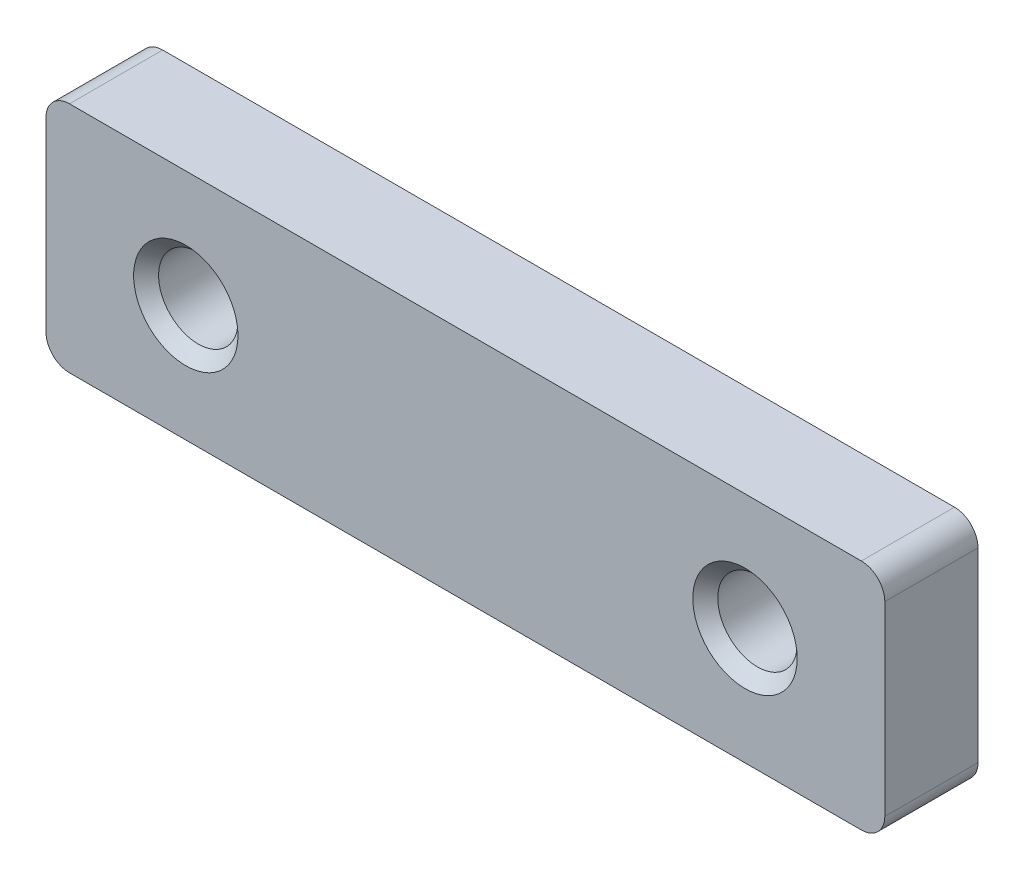
SolidWorks part; units mm, degrees
material "6061 Alloy"
ref_plane "Front Plane" through (0, 0, 0) normal (0, 0, 1) x (1, 0, 0)
ref_plane "Top Plane" through (0, 0, 0) normal (0, 1, 0) x (1, 0, 0)
ref_plane "Right Plane" through (0, 0, 0) normal (1, 0, 0) x (0, 0, -1)
sketch "Sketch1" plane through (0, 0, 0) normal (0, 0, 1) x (1, 0, 0)
  line L1 (-28.575, 7.9375) -> (28.575, 7.9375)
  line L2 (-28.575, 7.9375) -> (-28.575, -7.9375)
  line L3 (-28.575, -7.9375) -> (28.575, -7.9375)
  line L4 (28.575, 7.9375) -> (28.575, -7.9375)
  point P4 (0, 7.9375)
  point P5 (28.575, 0)
  dimension "D1" = 15.875
  dimension "D2" = 57.15
extrude "Boss-Extrude1" add sketch "Sketch1" against normal blind 6.35
hole_wizard "1/4-28 Tapped Hole1" positions "Sketch3" profile "Sketch2" tap size "1/4-28" standard "Ansi Inch" end condition through all
sketch "Sketch3" plane through (0, 0, 0) normal (0, 0, 1) x (1, 0, 0)
  point P0 (19.05, 0)
  point P1 (-19.05, 0)
  dimension "D1" = 19.05
  dimension "D2" = 19.05
sketch "Sketch2" plane through (19.05, 0, 0) normal (1, 0, 0) x (0, -1, 0)
  line L0 (0, 0) -> (0, 6.35)
  line L1 (0, 6.35) -> (3.556, 6.35)
  line L2 (2.7051, 5.4991) -> (2.7051, 0.8509)
  line L3 (2.7051, 0.8509) -> (3.556, 0)
  line L5 (3.556, 0) -> (0, 0)
  line L6 (-2.7051, 0.8509) -> (-3.556, 0) construction
  line L7 (3.556, 6.35) -> (2.7051, 5.4991)
  line L8 (-3.556, 6.35) -> (-2.7051, 5.4991) construction
  line L11 (0, -6.35) -> (0, 107.95) construction
  dimension "Thread Major Dia." = 5.4102
  dimension "Thru Tap Drill Depth" = 6.35
  dimension "Near C'Sink Dia." = 7.112
  dimension "Near C'Sink Angle" = 90
  dimension "Far C'Sink Dia." = 7.112
  dimension "Far C'Sink Angle" = 90
fillet "Fillet1" radius 1.6002 4 edges at (28.575, 7.9375, -3.175) (28.575, -7.9375, -3.175) (-28.575, 7.9375, -3.175) (-28.575, -7.9375, -3.175)
